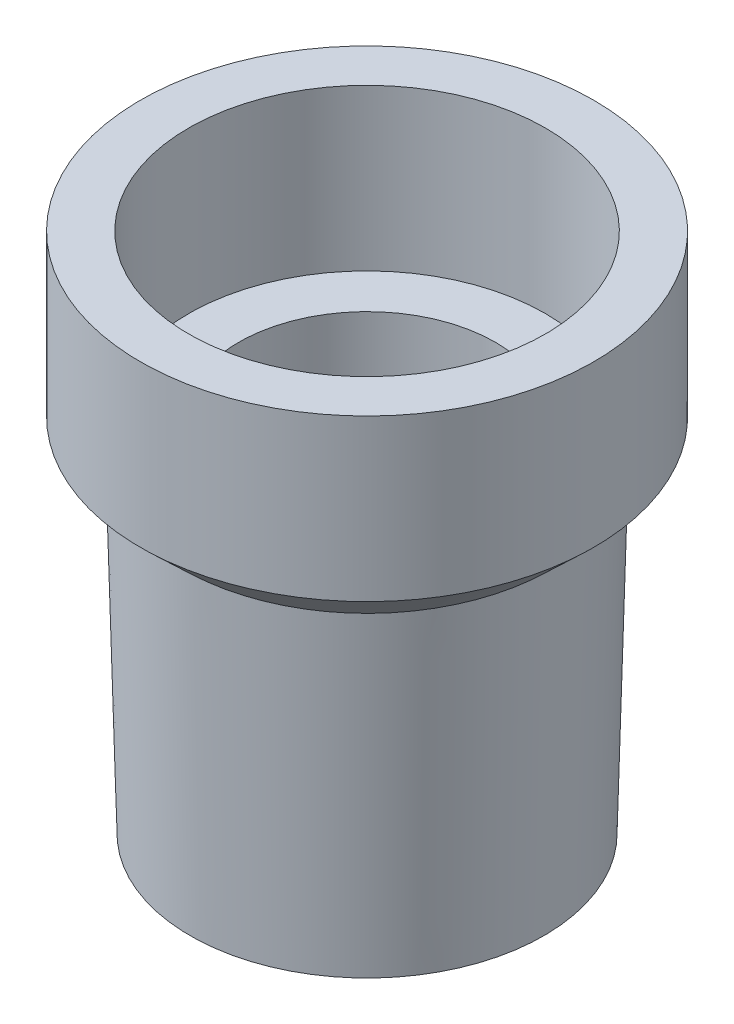
SolidWorks part; units mm, degrees
ref_plane "Front Plane" through (0, 0, 0) normal (0, 0, 1) x (1, 0, 0)
ref_plane "Top Plane" through (0, 0, 0) normal (0, 1, 0) x (1, 0, 0)
ref_plane "Right Plane" through (0, 0, 0) normal (1, 0, 0) x (0, 0, -1)
sketch "Sketch1" plane through (0, 0, 0) normal (0, 0, 1) x (1, 0, 0)
  line L0 (0, 0) -> (0, 67.1474) construction
  line L4 (11.1, 22.4732) -> (11.1, 32.4732)
  line L5 (11.1, 32.4732) -> (14.1, 32.4732)
  line L6 (14.1, 32.4732) -> (14.1, 22.4732)
  line L7 (14.1, 22.4732) -> (11.5, 20)
  line L8 (11.5, 20) -> (11, 0)
  line L9 (11, 0) -> (8, 0)
  line L10 (11.1, 22.4732) -> (8, 22.4732)
  line L11 (8, 22.4732) -> (8, 0)
  point P4 (0, 0)
  point P5 (0, 0)
  point P13 (0, 0)
  point P14 (0.9822, 22.5683)
  dimension "D1" = 22.2
  dimension "D2" = 3
  dimension "D3" = 3
  dimension "D4" = 22
  dimension "D5" = 23
  dimension "D6" = 20
  dimension "D7" = 10
  dimension "D8" = 135
revolve "Revolve1" add sketch "Sketch1" angle 360 about L0
